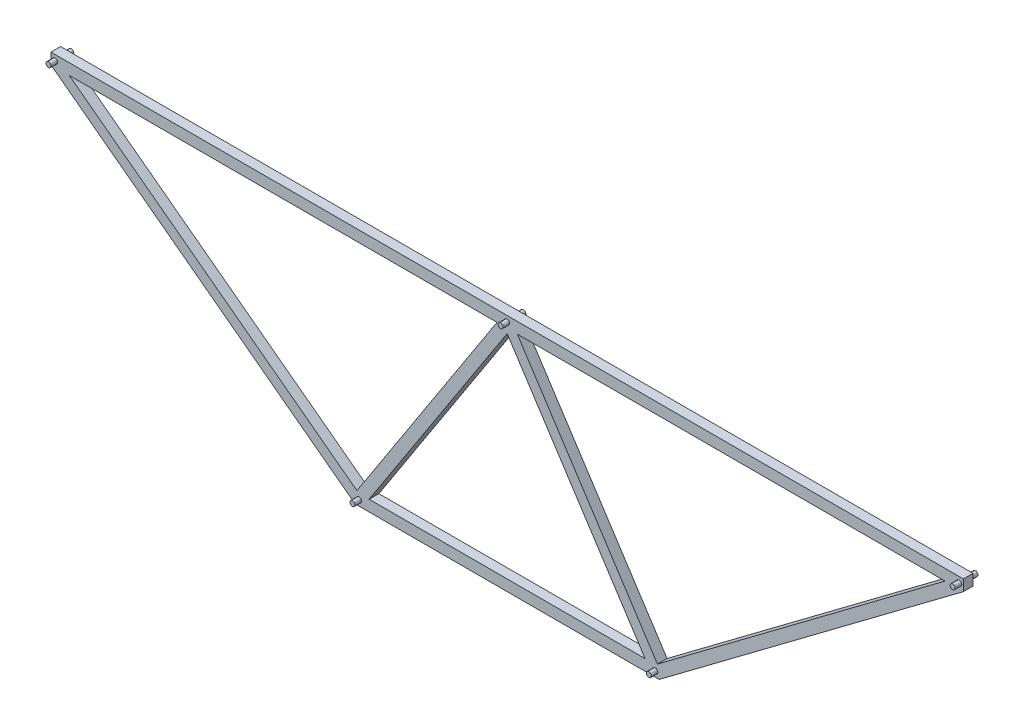
SolidWorks part; units mm, degrees
material "ASTM A36 Steel"
ref_plane "Front Plane" through (0, 0, 0) normal (0, 0, 1) x (1, 0, 0)
ref_plane "Top Plane" through (0, 0, 0) normal (0, 1, 0) x (1, 0, 0)
ref_plane "Right Plane" through (0, 0, 0) normal (1, 0, 0) x (0, 0, -1)
sketch "Sketch1" plane through (0, 0, 0) normal (0, 0, 1) x (1, 0, 0)
  line L2 (0, 0) -> (0, -14.49)
  line L9 (-200, -300) -> (200, -300)
  line L10 (-200, -300) -> (-200, -314.49)
  line L11 (-200, -314.49) -> (200, -314.49)
  line L12 (200, -300) -> (200, -314.49)
  line L20 (0, -314.49) -> (0, -300) construction
  line L21 (-200, -307.245) -> (200, -307.245) construction
  line L22 (-600, -7.245) -> (0, -7.245) construction
  line L23 (600, -14.49) -> (591.306, -2.898)
  line L30 (-200, -314.49) -> (-600, -14.49)
  line L31 (-200, -314.49) -> (-191.306, -302.898)
  line L32 (-600, -14.49) -> (-591.306, -2.898)
  line L33 (-196.6292, -309.9956) -> (0, -7.245) construction
  line L34 (6.076, -11.1912) -> (-190.5532, -313.9418)
  line L35 (6.076, -11.1912) -> (-6.076, -3.2988)
  line L36 (-6.076, -3.2988) -> (-202.7052, -306.0494)
  line L37 (-190.5532, -313.9418) -> (-202.7052, -306.0494)
  line L38 (-191.306, -302.898) -> (-591.306, -2.898)
  line L39 (600, 0) -> (-600, 0)
  line L40 (0, 0) -> (0, -14.49)
  line L41 (600, -14.49) -> (-600, -14.49)
  line L42 (-600, 0) -> (-600, -14.49)
  line L43 (191.306, -302.898) -> (591.306, -2.898)
  line L44 (200, -314.49) -> (191.306, -302.898)
  line L45 (200, -314.49) -> (600, -14.49)
  line L46 (-6.076, -11.1912) -> (6.076, -3.2988)
  line L47 (6.076, -3.2988) -> (202.7052, -306.0494)
  line L48 (190.5532, -313.9418) -> (202.7052, -306.0494)
  line L49 (-6.076, -11.1912) -> (190.5532, -313.9418)
  line L50 (600, 0) -> (600, -14.49)
  line L51 (0, -7.245) -> (600, -7.245) construction
  line L52 (0, -7.245) -> (196.6292, -309.9956) construction
  dimension "D1" = 600
  dimension "D2" = 14.49
  dimension "D3" = 300
  dimension "D5" = 14.49
  dimension "D6" = 400
  dimension "D8" = 14.49
  dimension "D10" = 500
  dimension "D14" = 361
  dimension "D15" = 14.49
extrude "Boss-Extrude2" add sketch "Sketch1" along normal mid plane 12.75 contours L39 L42 L32 L38 L41 L36 L35 L2 | L49 L41 L36 L38 L9 L34 | L38 L41 L30 L10 L37 L36 L9 | L34 L49 L9 L43 L47 L41 | L50 L39 L2 L46 L47 L41 L43 L23 | L48 L12 L45 L41 L43 L47 L9 | L49 L9 L34 L37 L31 L11 L44 L48 | L47 L46 L35 L34 L41 | L49 L46 L35 L36 L41 | L41 L34 L35 L2 | L46 L49 L41 L2 | L41 L49 L34 | L47 L43 L9 | L9 L47 L12 | L12 L48 L47 | L48 L44 L12 | L44 L48 L12 L47 L9 L43 | L9 L49 L48 L44 L43 | L43 L41 L23 | L41 L38 L32 | L38 L31 L37 L34 L9 | L31 L37 L10 | L37 L10 L36 | L9 L38 L36 | L36 L9 L10 | L31 L38 L9 L36 L10 L37
sketch "Sketch3" plane through (0, 0, 0) normal (0, 0, 1) x (1, 0, 0)
  line L0 (600, -14.49) -> (591.306, -2.898) construction
  line L1 (-200, -307.245) -> (200, -307.245) construction
  line L2 (0, -7.245) -> (600, -7.245) construction
  line L3 (0, -7.245) -> (196.6292, -309.9956) construction
  line L4 (-196.6292, -309.9956) -> (0, -7.245) construction
  line L5 (-600, -7.245) -> (0, -7.245) construction
  line L6 (-600, -14.49) -> (-591.306, -2.898) construction
  line L7 (600, -14.49) -> (591.306, -2.898) construction
  line L8 (-200, -307.245) -> (200, -307.245) construction
  line L9 (0, -7.245) -> (600, -7.245) construction
  line L10 (0, -7.245) -> (196.6292, -309.9956) construction
  line L11 (-196.6292, -309.9956) -> (0, -7.245) construction
  line L12 (-600, -7.245) -> (0, -7.245) construction
  line L13 (-600, -14.49) -> (-591.306, -2.898) construction
  circle A0 centre (0, -7.245) radius 3.3
  circle A1 centre (-194.8428, -307.245) radius 3.3
  circle A2 centre (194.8428, -307.245) radius 3.3
  circle A3 centre (594.5662, -7.245) radius 3.3
  circle A4 centre (-594.5663, -7.245) radius 3.3
  point P12 (-194.8428, -307.245)
  point P13 (194.8428, -307.245)
  point P16 (594.5662, -7.245)
  point P22 (-594.5663, -7.245)
  dimension "D1" = 6.6
extrude "Boss-Extrude3" add sketch "Sketch3" along normal mid plane 29.95 contours A4 | A1 | A2 | A0 | A3
